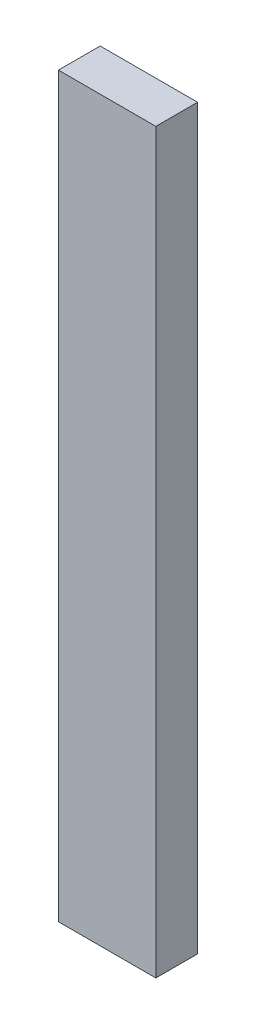
SolidWorks part; units mm, degrees
ref_plane "Front Plane" through (0, 0, 0) normal (0, 0, 1) x (1, 0, 0)
ref_plane "Top Plane" through (0, 0, 0) normal (0, 1, 0) x (1, 0, 0)
ref_plane "Right Plane" through (0, 0, 0) normal (1, 0, 0) x (0, 0, -1)
sketch "Sketch1" plane through (0, 0, 0) normal (0, 0, 1) x (1, 0, 0)
  line L1 (-292.1, 1149.35) -> (-203.2, 1149.35)
  line L2 (-292.1, 1149.35) -> (-292.1, 476.25)
  line L3 (-292.1, 476.25) -> (-203.2, 476.25)
  line L4 (-203.2, 1149.35) -> (-203.2, 476.25)
  dimension "D1" = 88.9
extrude "Boss-Extrude1" add sketch "Sketch1" along normal blind 38.1
